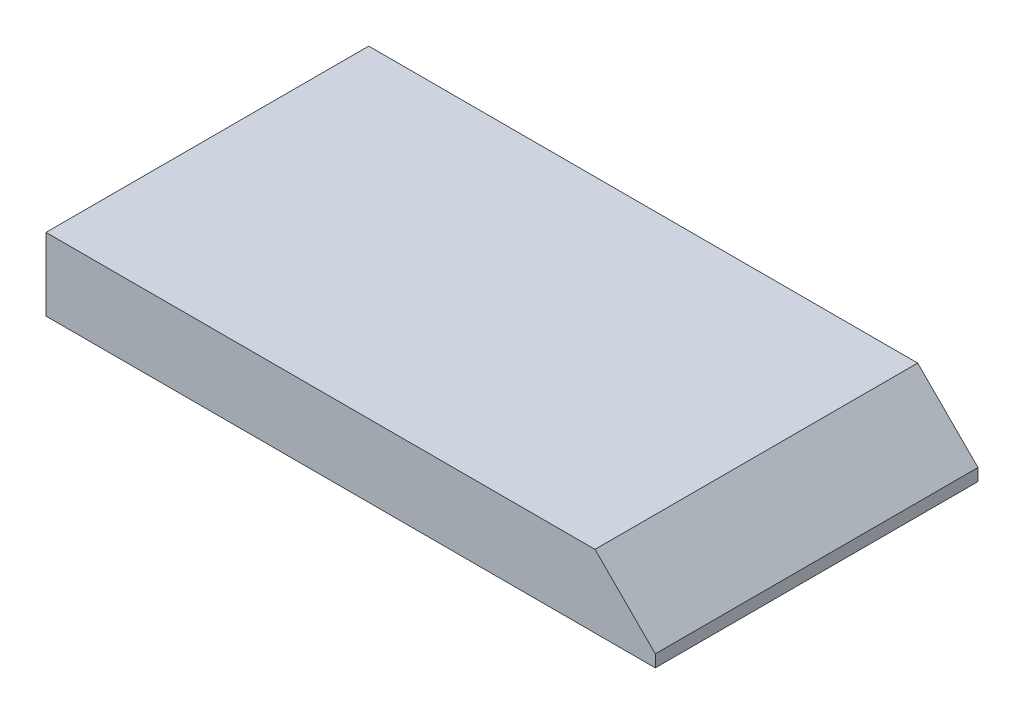
SolidWorks part; units mm, degrees
ref_plane "Front Plane" through (0, 0, 0) normal (0, 0, 1) x (1, 0, 0)
ref_plane "Top Plane" through (0, 0, 0) normal (0, 1, 0) x (1, 0, 0)
ref_plane "Right Plane" through (0, 0, 0) normal (1, 0, 0) x (0, 0, -1)
sketch "Sketch1" plane through (0, 0, 0) normal (0, 0, 1) x (1, 0, 0)
  line L0 (100, -9.8995) -> (90.1005, 0)
  line L1 (0, 0) -> (90.1005, 0)
  line L2 (0, 0) -> (0, -11.8995)
  line L3 (0, -11.8995) -> (100, -11.8995)
  line L4 (100, -9.8995) -> (100, -11.8995)
  point P5 (100, -9.8995)
  dimension "D1" = 14
  dimension "D2" = 100
  dimension "D3" = 2
  dimension "D4" = 45
extrude "Boss-Extrude1" add sketch "Sketch1" along normal blind 52.96
